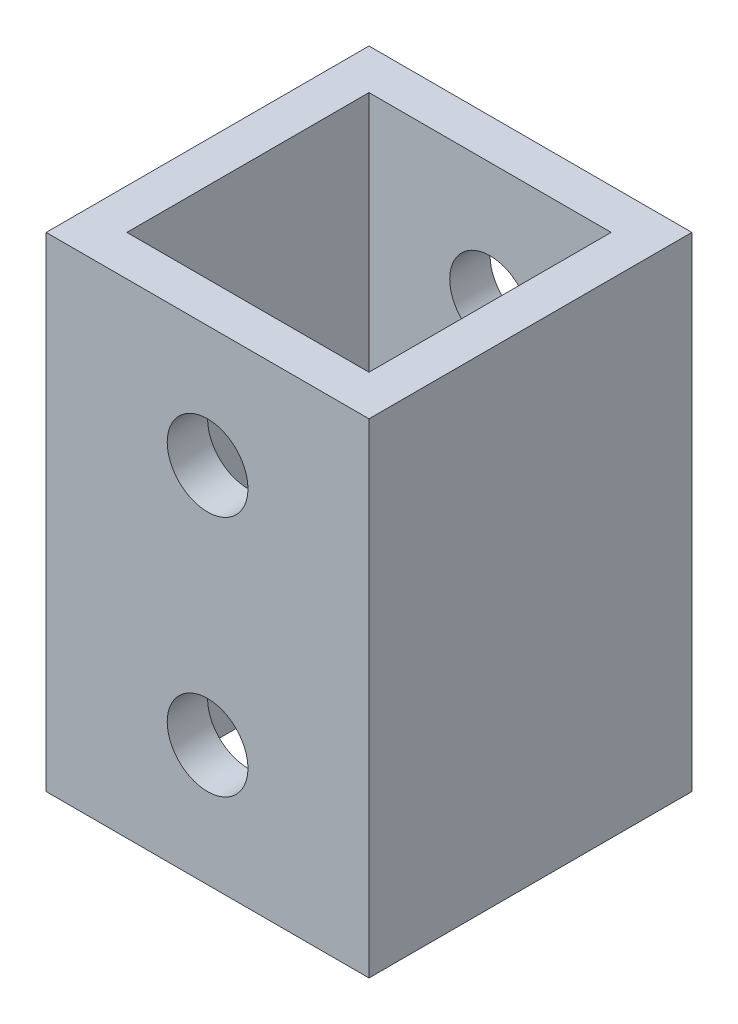
SolidWorks part; units mm, degrees
ref_plane "Front Plane" through (0, 0, 0) normal (0, 0, 1) x (1, 0, 0)
ref_plane "Top Plane" through (0, 0, 0) normal (0, 1, 0) x (1, 0, 0)
ref_plane "Right Plane" through (0, 0, 0) normal (1, 0, 0) x (0, 0, -1)
sketch "Sketch1" plane through (0, 0, 0) normal (0, 1, 0) x (1, 0, 0)
  line L1 (-12.7, 12.7) -> (12.7, 12.7)
  line L2 (-12.7, 12.7) -> (-12.7, -12.7)
  line L3 (-12.7, -12.7) -> (12.7, -12.7)
  line L4 (12.7, 12.7) -> (12.7, -12.7)
  line L5 (-12.7, 12.7) -> (12.7, -12.7) construction
  line L6 (-12.7, -12.7) -> (12.7, 12.7) construction
  line L7 (-9.525, 9.525) -> (9.525, 9.525)
  line L8 (-9.525, 9.525) -> (-9.525, -9.525)
  line L9 (-9.525, -9.525) -> (9.525, -9.525)
  line L10 (9.525, 9.525) -> (9.525, -9.525)
  line L11 (-9.525, 9.525) -> (9.525, -9.525) construction
  line L12 (-9.525, -9.525) -> (9.525, 9.525) construction
  point P0 (0, 0)
  point P6 (0, 0)
  dimension "D1" = 25.4
  dimension "D2" = 25.4
  dimension "D3" = 19.05
extrude "Boss-Extrude1" add sketch "Sketch1" along normal blind 38.1
sketch "Sketch2" plane through (0, 0, -12.7) normal (0, 0, -1) x (-1, 0, 0)
  line L2 (-12.7, 38.1) -> (12.7, 38.1) construction
  circle A0 centre (0, 28.575) radius 3.175
  circle A1 centre (0, 9.525) radius 3.175
  point P8 (-3.1278, 12.2722)
  dimension "D1" = 6.35
  dimension "D2" = 19.05
  dimension "D3" = 9.525
extrude "Cut-Extrude1" cut sketch "Sketch2" against normal blind 25.4
